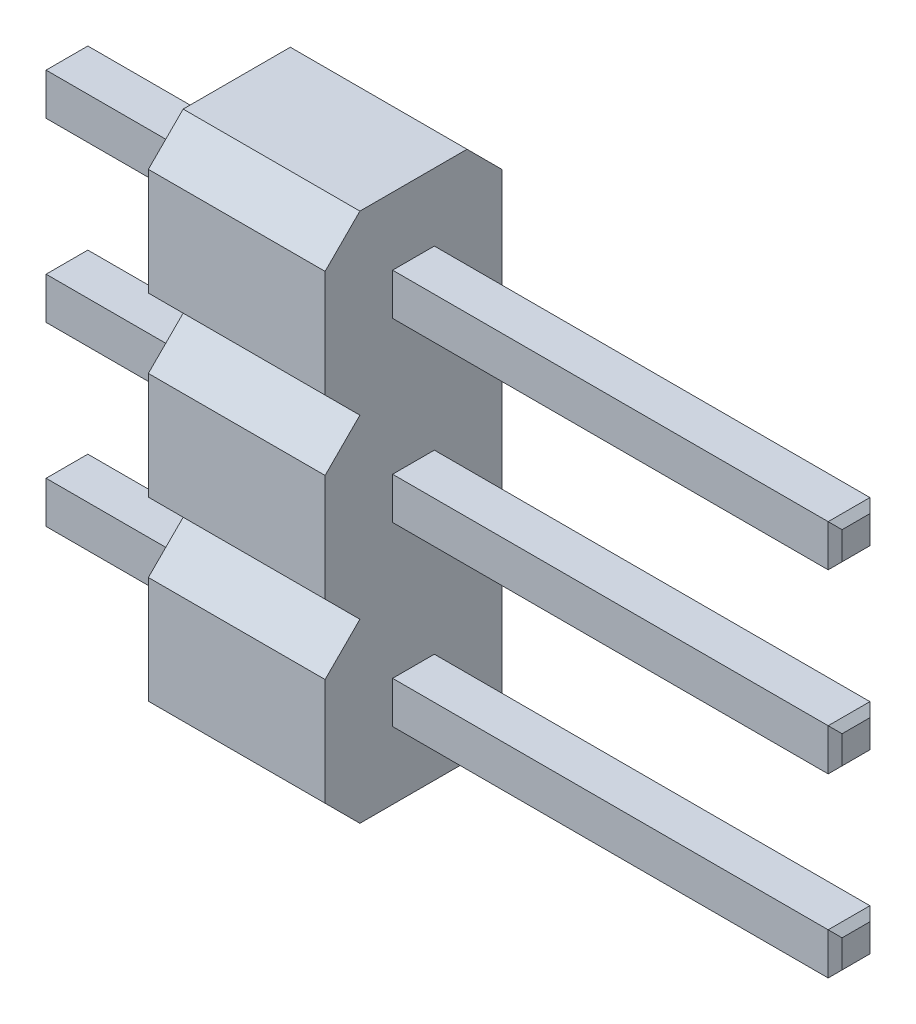
SolidWorks part; units mm, degrees
ref_plane "Front Plane" through (0, 0, 0) normal (0, 0, 1) x (1, 0, 0)
ref_plane "Top Plane" through (0, 0, 0) normal (0, 1, 0) x (1, 0, 0)
ref_plane "Right Plane" through (0, 0, 0) normal (1, 0, 0) x (0, 0, -1)
sketch "Sketch1" plane through (0, 0, 0) normal (1, 0, 0) x (0, 0, -1)
  line L0 (0, 0) -> (-1.27, 0) construction
  line L5 (-1.27, 0) -> (-1.27, 1.27) construction
  line L6 (-2.04, 1.27) -> (-0.5, 1.27)
  line L7 (-0.5, 1.27) -> (0, 0.77)
  line L8 (0, 0.77) -> (0, -0.77)
  line L9 (-2.54, 0.77) -> (-2.54, -0.77)
  line L10 (-2.04, 1.27) -> (-2.54, 0.77)
  line L11 (-0.5, -1.27) -> (0, -0.77)
  line L12 (-2.04, -1.27) -> (-0.5, -1.27)
  line L13 (-2.04, -1.27) -> (-2.54, -0.77)
  point P13 (-2.54, 0)
  dimension "D1" = 1.27
  dimension "D2" = 45
  dimension "D3" = 0.5
extrude "Plastic" add sketch "Sketch1" along normal blind 2.54
sketch "Sketch2" plane through (0, 0, 0) normal (0, 1, 0) x (1, 0, 0)
  line L0 (-2.54, -0.97) -> (-2.54, -1.57)
  line L1 (-2.54, -1.27) -> (8.9, -1.27) construction
  line L2 (0, -2.04) -> (0, -0.5) construction
  line L4 (-2.54, -1.57) -> (8.9, -1.57)
  line L6 (-2.54, -0.97) -> (8.9, -0.97)
  line L8 (8.9, -1.57) -> (8.9, -0.97)
  line L11 (-3.14, 3.36) -> (-3.14, -0.67) construction
  line L12 (-3.44, 3.36) -> (-3.44, -0.67) construction
  line L13 (-2.84, 3.36) -> (-2.84, -0.67) construction
  line L14 (2.54, -0.5) -> (2.54, -2.04) construction
  arc A3 (-3.44, -0.67) -> (-2.54, -1.57) centre (-2.54, -0.67) ccw construction
  arc A4 (-3.14, -0.67) -> (-2.54, -1.27) centre (-2.54, -0.67) ccw construction
  arc A5 (-2.84, -0.67) -> (-2.54, -0.97) centre (-2.54, -0.67) ccw construction
  point P5 (0, -1.27)
  dimension "D1" = 5.08
  dimension "D4" = 8.9
  dimension "D2" = 0.3
  dimension "D3" = 0.3
extrude "Contact" add sketch "Sketch2" along normal mid plane 0.6
chamfer "Chamfer1" distance 0.1 angle 45 8 edges at (8.9, 0.3, 1.27) (8.9, 0, 1.57) (8.9, -0.3, 1.27) (8.9, 0, 0.97) (-2.54, -0.3, 1.27) (-2.54, 0, 0.97) (-2.54, 0.3, 1.27) (-2.54, 0, 1.57)
pattern_linear "LPattern1" count 3 spacing 2.54 along (0, 1, 0) of "Plastic", "Contact", "Chamfer1"
